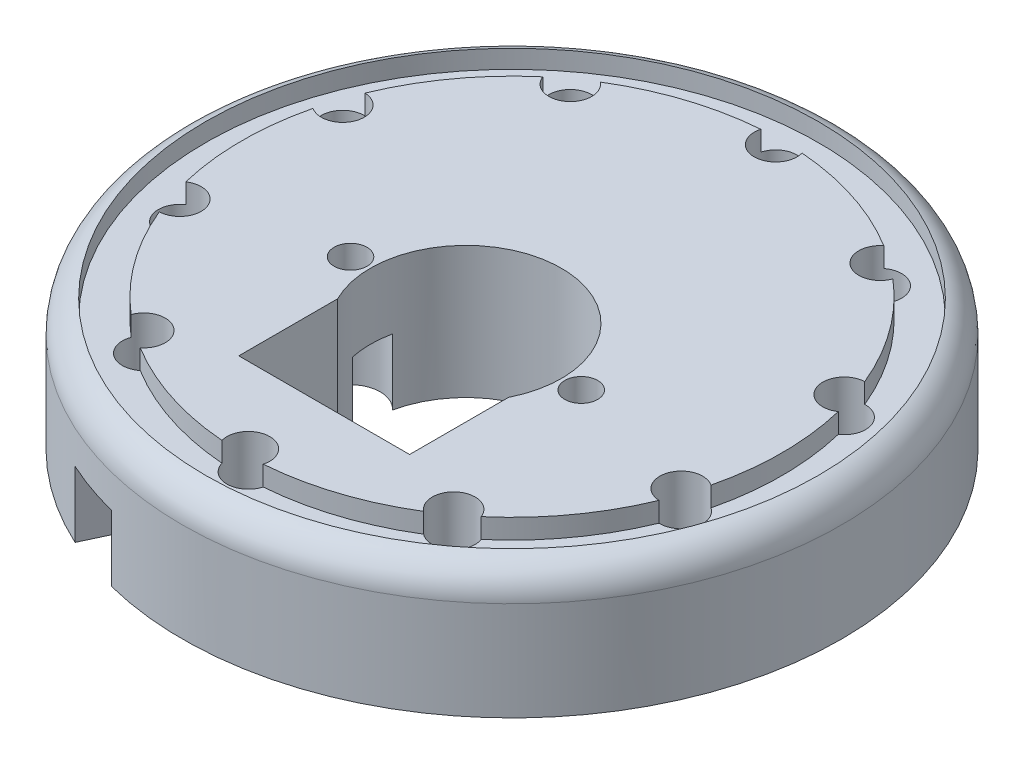
SolidWorks part; units mm, degrees
ref_plane "前视基准面" through (0, 0, 0) normal (0, 0, 1) x (1, 0, 0)
ref_plane "上视基准面" through (0, 0, 0) normal (0, 1, 0) x (1, 0, 0)
ref_plane "右视基准面" through (0, 0, 0) normal (1, 0, 0) x (0, 0, -1)
sketch "草图1" plane through (0, 0, 0) normal (0, 1, 0) x (1, 0, 0)
  circle A0 centre (0, 0) radius 50
extrude "凸台-拉伸1" add sketch "草图1" along normal blind 20
fillet "圆角1" radius 5 1 edges at (0, 20, 50)
sketch "草图2" plane through (0, 20, 0) normal (0, 1, 0) x (1, 0, 0)
  circle A0 centre (0, -7) radius 14.5
extrude "切除-拉伸1" cut sketch "草图2" against normal blind 20
sketch "草图3" plane through (0, 20, 0) normal (0, 1, 0) x (1, 0, 0)
  line L0 (-12.9615, -13.5) -> (12.9615, -13.5)
  line L3 (12.9615, -13.5) -> (12.9615, -28.5)
  line L4 (12.9615, -28.5) -> (-12.9615, -28.5)
  line L5 (-12.9615, -28.5) -> (-12.9615, -13.5)
  circle A0 centre (-17.5, -7) radius 2.5
  circle A1 centre (17.5, -7) radius 2.5
  circle A2 centre (0, -7) radius 14.5 construction
extrude "切除-拉伸2" cut sketch "草图3" against normal blind 20
sketch "草图4" plane through (0, 20, 0) normal (0, 1, 0) x (1, 0, 0)
  circle A0 centre (0, 40) radius 3.25
  circle A1 centre (23.5114, 32.3607) radius 3.25
  circle A2 centre (38.0423, 12.3607) radius 3.25
  circle A3 centre (38.0423, -12.3607) radius 3.25
  circle A4 centre (23.5114, -32.3607) radius 3.25
  circle A5 centre (0, -40) radius 3.25
  circle A6 centre (-23.5114, -32.3607) radius 3.25
  circle A7 centre (-38.0423, -12.3607) radius 3.25
  circle A8 centre (-38.0423, 12.3607) radius 3.25
  circle A9 centre (-23.5114, 32.3607) radius 3.25
  point P23 (0, 0)
  dimension "D1" = 10
extrude "切除-拉伸3" cut sketch "草图4" against normal through all
sketch "草图5" plane through (0, 0, 0) normal (0, -1, 0) x (1, 0, 0)
  circle A0 centre (0, 0) radius 36.75
  circle A1 centre (0, 0) radius 43.25
extrude "切除-拉伸4" cut sketch "草图5" against normal blind 10
sketch "草图7" plane through (0, 20, 0) normal (0, 1, 0) x (1, 0, 0)
  circle A1 centre (0, 0) radius 46.5
  circle A2 centre (0, 0) radius 41
extrude "切除-拉伸5" cut sketch "草图7" against normal blind 3
sketch "草图8" plane through (0, 0, 0) normal (0, -1, 0) x (1, 0, 0)
  line L0 (-12.9615, 28.5) -> (-22.0419, 47.9731)
  line L1 (-12.9615, 28.5) -> (-2.9615, 28.5)
  line L2 (-12.9615, 28.5) -> (12.9615, 28.5) construction
  line L5 (-2.9615, 28.5) -> (-13.1104, 50.2644)
  line L6 (-22.0419, 47.9731) -> (-13.1104, 50.2644)
extrude "切除-拉伸6" cut sketch "草图8" against normal up to surface (10 mm away) up to face at (-12.2134, 10, 37.5889)
sketch "草图9" plane through (0, 0, 0) normal (0, -1, 0) x (1, 0, 0)
  circle A0 centre (-17.5, 7) radius 4.5
  circle A1 centre (17.5, 7) radius 4.5
extrude "切除-拉伸7" cut sketch "草图9" against normal blind 10
sketch "草图10" plane through (0, 0, 0) normal (0, -1, 0) x (1, 0, 0)
  circle A0 centre (0, -30) radius 3
  circle A1 centre (-25.9808, 15) radius 3
  circle A2 centre (25.9808, 15) radius 3
  point P11 (0, 0)
  dimension "D1" = 3
extrude "凸台-拉伸2" add sketch "草图10" along normal blind 5
